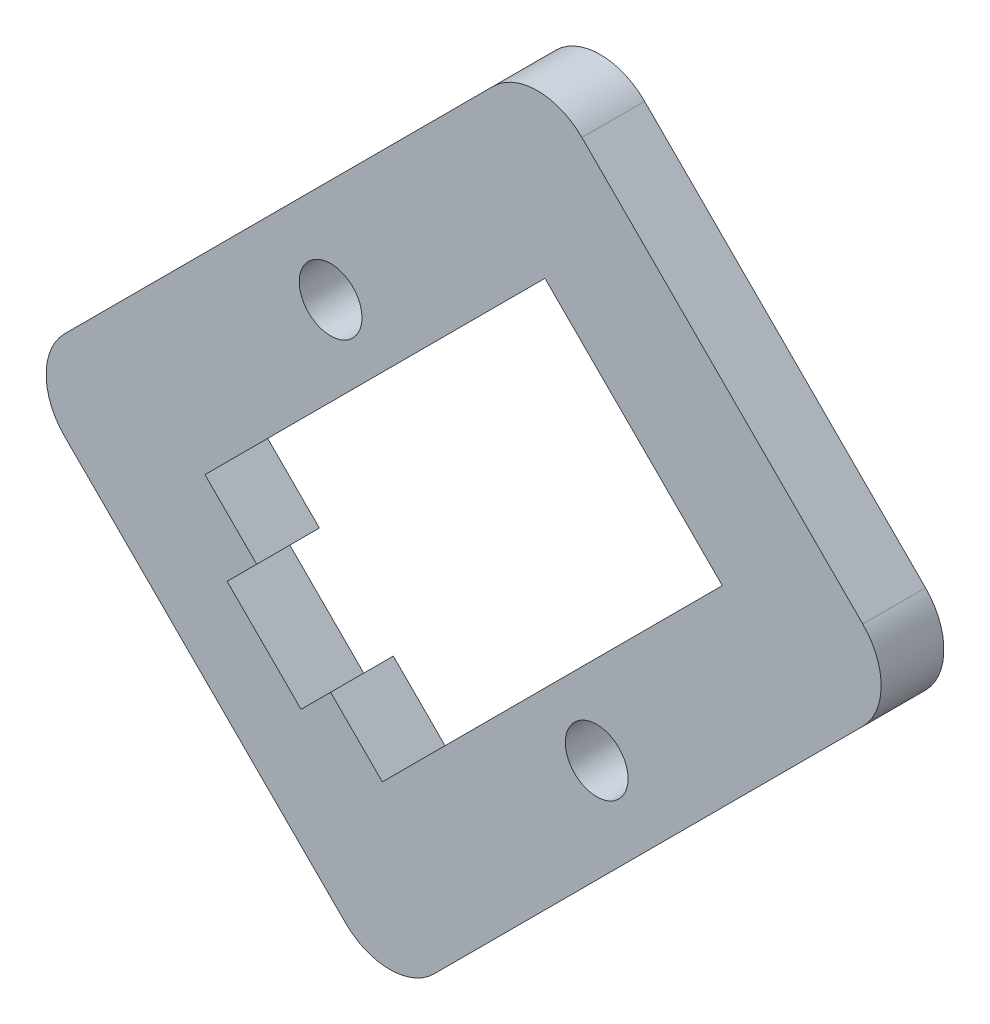
SolidWorks part; units mm, degrees
ref_plane "前基準面" through (0, 0, 0) normal (0, 0, 1) x (1, 0, 0)
ref_plane "上基準面" through (0, 0, 0) normal (0, 1, 0) x (1, 0, 0)
ref_plane "右基準面" through (0, 0, 0) normal (1, 0, 0) x (0, 0, -1)
sketch "草圖1" plane through (0, 0, 0) normal (0, 0, 1) x (1, 0, 0)
  line L0 (97.7716, 7.2304) -> (118.2777, 27.7365) construction
  line L1 (91.4076, 15.0085) -> (92.8219, 16.4228) construction
  line L2 (92.8219, 16.4228) -> (95.2967, 13.9479) construction
  line L3 (95.2967, 13.9479) -> (111.5602, 30.2114) construction
  line L4 (111.5602, 30.2114) -> (103.0749, 38.6967) construction
  line L5 (103.0749, 38.6967) -> (86.8115, 22.4332) construction
  line L6 (86.8115, 22.4332) -> (89.2863, 19.9583) construction
  line L7 (89.2863, 19.9583) -> (87.8721, 18.544) construction
  line L8 (87.8721, 18.544) -> (91.4076, 15.0085) construction
  line L9 (80.094, 24.9081) -> (100.6, 45.4142) construction
  line L10 (97.7716, 7.2304) -> (118.2777, 27.7365)
  line L11 (91.4076, 15.0085) -> (92.8219, 16.4228)
  line L12 (92.8219, 16.4228) -> (95.2967, 13.9479)
  line L13 (95.2967, 13.9479) -> (111.5602, 30.2114)
  line L14 (111.5602, 30.2114) -> (103.0749, 38.6967)
  line L15 (103.0749, 38.6967) -> (86.8115, 22.4332)
  line L16 (86.8115, 22.4332) -> (89.2863, 19.9583)
  line L17 (89.2863, 19.9583) -> (87.8721, 18.544)
  line L18 (87.8721, 18.544) -> (91.4076, 15.0085)
  line L19 (80.094, 24.9081) -> (100.6, 45.4142)
  line L20 (80.094, 20.6654) -> (93.529, 7.2304)
  line L21 (104.8427, 45.4142) -> (118.2777, 31.9791)
  arc A0 (93.529, 7.2304) -> (97.7716, 7.2304) centre (95.6503, 9.3517) ccw construction
  arc A1 (118.2777, 27.7365) -> (118.2777, 31.9791) centre (116.1564, 29.8578) ccw construction
  circle A2 centre (105.5498, 19.9583) radius 1.5 construction
  circle A3 centre (92.8219, 32.6863) radius 1.5 construction
  arc A4 (80.094, 24.9081) -> (80.094, 20.6654) centre (82.2153, 22.7868) ccw construction
  arc A5 (104.8427, 45.4142) -> (100.6, 45.4142) centre (102.7214, 43.2929) ccw construction
  arc A6 (93.529, 7.2304) -> (97.7716, 7.2304) centre (95.6503, 9.3517) ccw
  arc A7 (118.2777, 27.7365) -> (118.2777, 31.9791) centre (116.1564, 29.8578) ccw
  circle A8 centre (105.5498, 19.9583) radius 1.5
  circle A9 centre (92.8219, 32.6863) radius 1.5
  arc A10 (80.094, 24.9081) -> (80.094, 20.6654) centre (82.2153, 22.7868) ccw
  arc A11 (104.8427, 45.4142) -> (100.6, 45.4142) centre (102.7214, 43.2929) ccw
extrude "填料-伸長1" add sketch "草圖1" along normal blind 3
